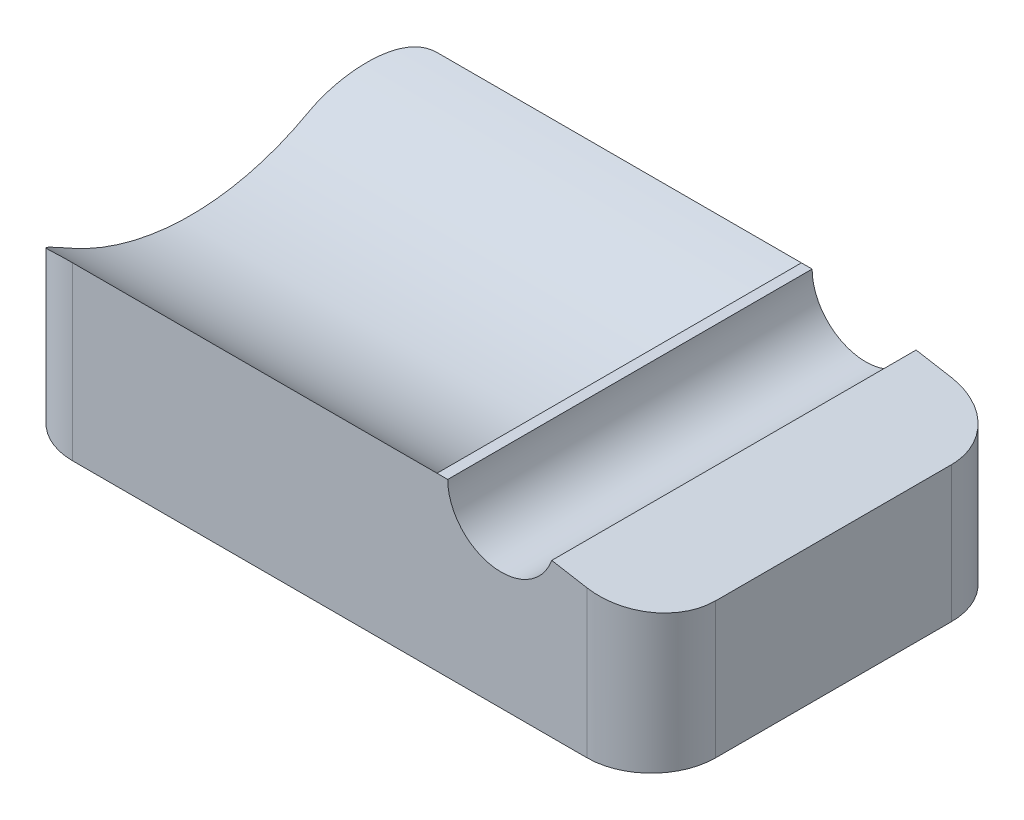
SolidWorks part; units mm, degrees
ref_plane "Front Plane" through (0, 0, 0) normal (0, 0, 1) x (1, 0, 0)
ref_plane "Top Plane" through (0, 0, 0) normal (0, 1, 0) x (1, 0, 0)
ref_plane "Right Plane" through (0, 0, 0) normal (1, 0, 0) x (0, 0, -1)
sketch "Sketch1" plane through (0, 0, 0) normal (0, 1, 0) x (1, 0, 0)
  line L1 (0, 0) -> (60, 0)
  line L2 (0, 0) -> (0, 34)
  line L3 (0, 34) -> (60, 34)
  line L4 (60, 0) -> (60, 34)
  dimension "D1" = 34
  dimension "D2" = 60
extrude "Boss-Extrude1" add sketch "Sketch1" along normal blind 16
sketch "Sketch3" plane through (0, 0, 0) normal (-1, 0, 0) x (0, 0, 1)
  line L0 (-34, 16) -> (-32, 18)
  line L1 (-2, 18) -> (0, 16)
  line L2 (0, 16) -> (0, 0) construction
  line L3 (-34, 16) -> (0, 16) construction
  line L4 (-34, 16) -> (-29.6886, 16)
  line L5 (0, 16) -> (-4.3114, 16)
  arc A0 (-32, 18) -> (-29.6886, 16) centre (-17, 33) ccw
  arc A1 (-4.3114, 16) -> (-2, 18) centre (-17, 33) ccw
  dimension "D1" = 45
  dimension "D2" = 45
  dimension "D3" = 2
sketch "Sketch6" plane through (0, 0, 0) normal (-1, 0, 0) x (0, 0, 1)
  line L0 (-34, 16) -> (0, 16) construction
  circle A3 centre (-17, 31) radius 22.6716
  point P2 (-17, 31.1346)
  point P3 (0, 0)
  dimension "D1" = 15
extrude "Cut-Extrude4" cut sketch "Sketch6" against normal blind 40
sketch "Sketch2" plane through (0, 0, 0) normal (0, 0, 1) x (1, 0, 0)
  line L0 (40, 16) -> (60, 16) construction
  line L1 (0, 16) -> (0, 0) construction
  circle A0 centre (46, 16) radius 5
  dimension "D1" = 10
  dimension "D2" = 46
extrude "Cut-Extrude1" cut sketch "Sketch2" against normal through all
fillet "Fillet1" radius 6 4 edges at (0, 8, -34) (60, 8, -34) (60, 8, 0) (0, 8, 0)
sketch "Sketch5" plane through (0, 0, 0) normal (0, 0, 1) x (1, 0, 0)
  line L0 (50.7059, 14.3105) -> (60, 12.6927)
  line L1 (60, 16) -> (60, 0) construction
  line L2 (60, 12.6927) -> (60, 16)
  line L3 (60, 16) -> (51, 16)
  line L4 (51, 16) -> (50.7059, 14.3105)
  arc A0 (41, 16) -> (51, 16) centre (46, 16) ccw construction
extrude "Cut-Extrude3" cut sketch "Sketch5" against normal through all
sketch "Sketch7" plane through (0, 0, 0) normal (0, -1, 0) x (1, 0, 0)
  line L0 (13, -11) -> (13, -23)
  line L1 (13, -23) -> (12, -23)
  line L2 (12, -11) -> (13, -11)
  line L3 (8, -14.3142) -> (8, -22.5392) construction
  line L4 (0, -17) -> (76.8912, -17) construction
  line L5 (0, -28) -> (0, -6) construction
  arc A0 (12, -23) -> (12, -11) centre (14.5, -17) cw
  point P11 (0, 0)
  dimension "D1" = 1
  dimension "D2" = 5
  dimension "D3" = 12
  dimension "D4" = 13
extrude "Boss-Extrude2" add sketch "Sketch7" along normal blind 1
